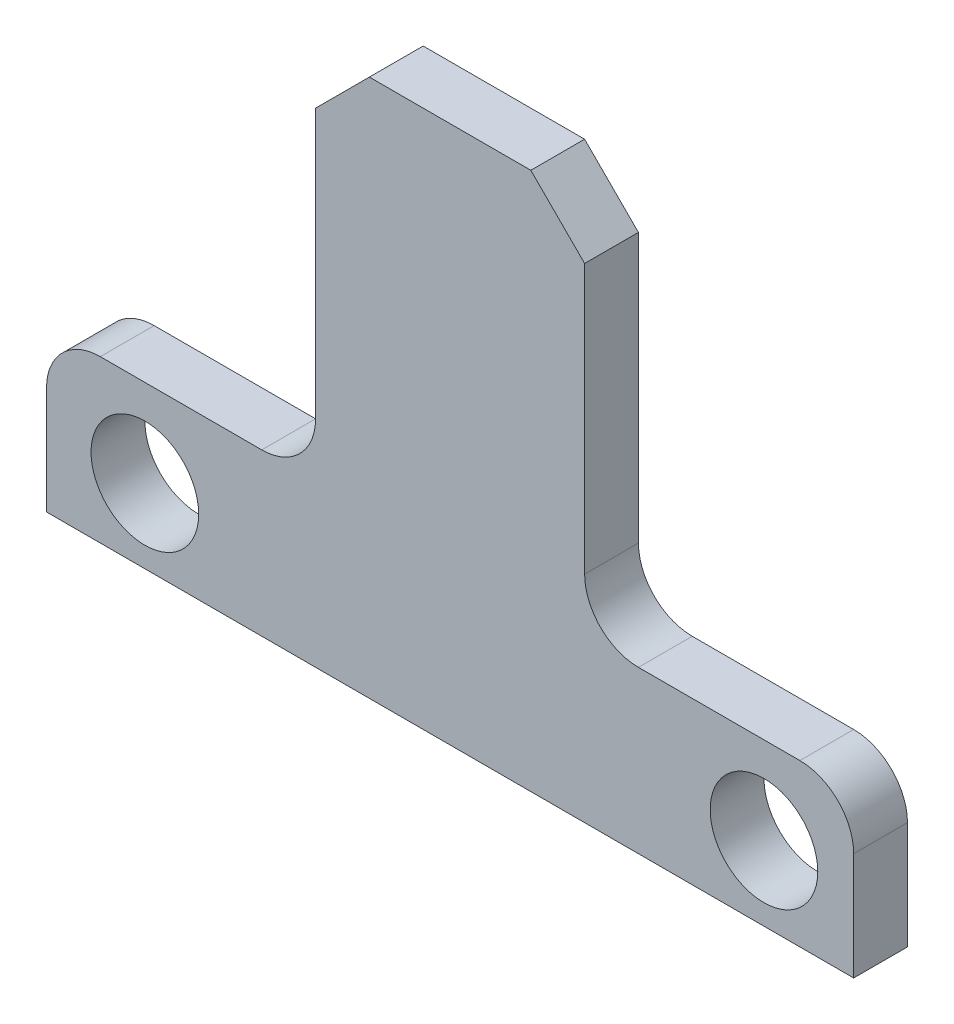
SolidWorks part; units mm, degrees
ref_plane "Front Plane" through (0, 0, 0) normal (0, 0, 1) x (1, 0, 0)
ref_plane "Top Plane" through (0, 0, 0) normal (0, 1, 0) x (1, 0, 0)
ref_plane "Right Plane" through (0, 0, 0) normal (1, 0, 0) x (0, 0, -1)
sketch "Sketch1" plane through (0, 0, 0) normal (0, 0, 1) x (1, 0, 0)
  line L1 (-33.2727, 35.6708) -> (-3.2727, 35.6708)
  line L2 (-43.2727, 25.6708) -> (-43.2727, -24.3292)
  line L3 (6.7273, 25.6708) -> (6.7273, -24.3292)
  line L4 (16.7273, -34.3292) -> (46.7273, -34.3292)
  line L5 (-53.2727, -34.3292) -> (-83.2727, -34.3292)
  line L6 (-93.2727, -44.3292) -> (-93.2727, -64.3292)
  line L7 (56.7273, -44.3292) -> (56.7273, -64.3292)
  line L8 (-93.2727, -64.3292) -> (56.7273, -64.3292)
  line L9 (-43.2727, 25.6708) -> (-33.2727, 35.6708)
  line L10 (-3.2727, 35.6708) -> (6.7273, 25.6708)
  arc A0 (-43.2727, -24.3292) -> (-53.2727, -34.3292) centre (-53.2727, -24.3292) cw
  arc A1 (6.7273, -24.3292) -> (16.7273, -34.3292) centre (16.7273, -24.3292) ccw
  arc A2 (-83.2727, -34.3292) -> (-93.2727, -44.3292) centre (-83.2727, -44.3292) ccw
  arc A3 (46.7273, -34.3292) -> (56.7273, -44.3292) centre (46.7273, -44.3292) cw
  circle A4 centre (-74.9963, -50.5463) radius 10
  circle A5 centre (40.0565, -50.5463) radius 10
  point P0 (40.0565, -50.5463)
  point P2 (-43.2727, 35.6708)
  point P3 (6.7273, 35.6708)
  dimension "D1" = 10
  dimension "D11" = 20
  dimension "D12" = 20
  dimension "D2" = 150
  dimension "D3" = 50
  dimension "D4" = 100
  dimension "D7" = 50
  dimension "D8" = 50
  dimension "D9" = 30
  dimension "D10" = 30
extrude "Boss-Extrude1" add sketch "Sketch1" along normal blind 10
